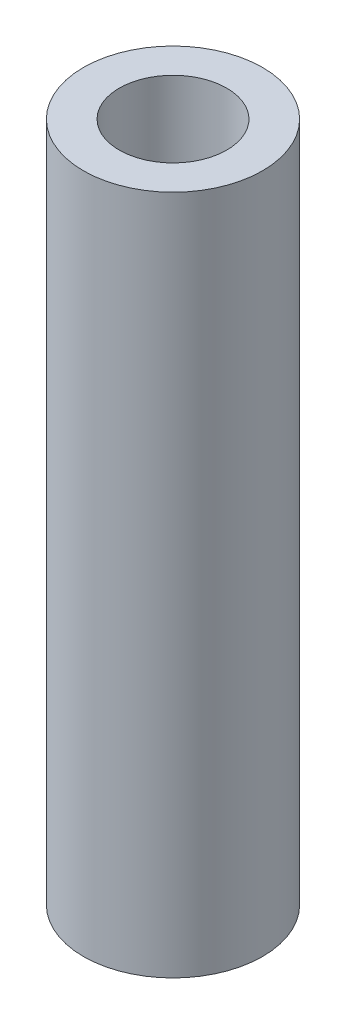
SolidWorks part; units mm, degrees
ref_plane "Front Plane" through (0, 0, 0) normal (0, 0, 1) x (1, 0, 0)
ref_plane "Top Plane" through (0, 0, 0) normal (0, 1, 0) x (1, 0, 0)
ref_plane "Right Plane" through (0, 0, 0) normal (1, 0, 0) x (0, 0, -1)
sketch "Sketch1" plane through (0, 0, 0) normal (0, 1, 0) x (1, 0, 0)
  circle A0 centre (0, 0) radius 3.81
  circle A1 centre (0, 0) radius 6.35
  dimension "D1" = 7.62
  dimension "D2" = 2.54
extrude "Boss-Extrude1" add sketch "Sketch1" along normal blind 48.26
